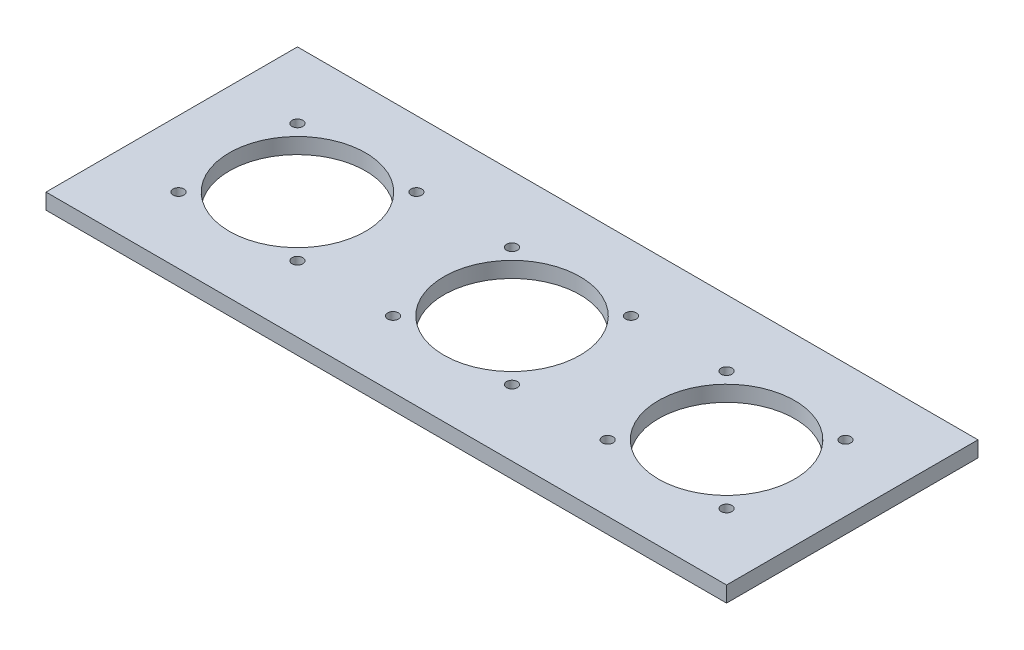
SolidWorks part; units mm, degrees
ref_plane "Front Plane" through (0, 0, 0) normal (0, 0, 1) x (1, 0, 0)
ref_plane "Top Plane" through (0, 0, 0) normal (0, 1, 0) x (1, 0, 0)
ref_plane "Right Plane" through (0, 0, 0) normal (1, 0, 0) x (0, 0, -1)
sketch "Sketch1" plane through (0, 0, 0) normal (0, 1, 0) x (1, 0, 0)
  line L1 (-206.248, -76.2) -> (206.248, -76.2)
  line L2 (-206.248, -76.2) -> (-206.248, 76.2)
  line L3 (-206.248, 76.2) -> (206.248, 76.2)
  line L4 (206.248, -76.2) -> (206.248, 76.2)
  line L5 (-206.248, -76.2) -> (206.248, 76.2) construction
  line L6 (-206.248, 76.2) -> (206.248, -76.2) construction
  point P0 (0, 0)
  dimension "D1" = 206.248
  dimension "D2" = 76.2
extrude "Boss-Extrude1" add sketch "Sketch1" along normal mid plane 9.525
sketch "Sketch2" plane through (0, 0, 0) normal (0, 1, 0) x (1, 0, 0)
  circle A0 centre (-130.048, 0) radius 41.275
  circle A1 centre (0, 0) radius 41.275
  circle A2 centre (130.048, 0) radius 41.275
  point P6 (0, 0)
  dimension "D1" = 82.55
  dimension "D2" = 82.55
  dimension "D3" = 82.55
  dimension "D4" = 130.048
  dimension "D5" = 260.096
extrude "Cut-Extrude2" cut sketch "Sketch2" against normal through all from offset 4.7625
hole_wizard "5/16-18 Tapped Hole1" positions "Sketch4" profile "Sketch3" tap size "5/16-18" standard "ANSI Inch"
sketch "Sketch4" plane through (0, 4.7625, 0) normal (0, 1, 0) x (1, 0, 0)
  line L0 (-166.0906, -36.0426) -> (-94.0054, -36.0426) construction
  line L1 (-94.0054, -36.0426) -> (-94.0054, 36.0426) construction
  line L2 (-94.0054, 36.0426) -> (-166.0906, 36.0426) construction
  line L3 (-166.0906, 36.0426) -> (-166.0906, -36.0426) construction
  line L4 (0, 0) -> (-94.0054, -36.0426) construction
  line L5 (206.248, -76.2) -> (206.248, 76.2) construction
  point P0 (-166.0906, -36.0426)
  point P1 (-94.0054, -36.0426)
  point P3 (-166.0906, 36.0426)
  point P5 (-94.0054, 36.0426)
  dimension "D1" = 300.2534
  dimension "D2" = 372.3386
  dimension "D3" = 40.1574
  dimension "D4" = 112.2426
sketch "Sketch3" plane through (-166.0906, 4.7625, 36.0426) normal (1, 0, 0) x (0, 0, 1)
  line L0 (0, 0) -> (0, 11.4861)
  line L1 (0, 11.4861) -> (3.2639, 9.525)
  line L2 (3.2639, 9.525) -> (3.2639, 0)
  line L5 (3.2639, 0) -> (0, 0)
  line L10 (0, 11.4861) -> (-3.2639, 9.525) construction
  line L11 (0, -6.35) -> (0, 107.95) construction
  dimension "Tap Drill Dia." = 6.5278
  dimension "Tap Drill Depth" = 9.525
  dimension "Drill Angle" = 118
cosmetic thread "Hole Thread1" parameters "D1"=15.875, "D2"=7.9375
cosmetic thread "Hole Thread2" parameters "D1"=15.875, "D2"=7.9375
cosmetic thread "Hole Thread3" parameters "D1"=15.875, "D2"=7.9375
cosmetic thread "Hole Thread4" parameters "D1"=15.875, "D2"=7.9375
hole_wizard "5/16-18 Tapped Hole2" positions "Sketch6" profile "Sketch5" tap size "5/16-18" standard "ANSI Inch"
sketch "Sketch6" plane through (0, 4.7625, 0) normal (0, 1, 0) x (1, 0, 0)
  line L0 (-36.0426, -36.0426) -> (36.0426, -36.0426) construction
  line L1 (36.0426, -36.0426) -> (36.0426, 36.0426) construction
  line L2 (36.0426, 36.0426) -> (-36.0426, 36.0426) construction
  line L3 (-36.0426, 36.0426) -> (-36.0426, -36.0426) construction
  line L4 (0, 0) -> (36.0426, -36.0426) construction
  circle A0 centre (-130.048, 0) radius 41.275 construction
  point P0 (-36.0426, -36.0426)
  point P1 (36.0426, -36.0426)
  point P3 (-36.0426, 36.0426)
  point P5 (36.0426, 36.0426)
  dimension "D1" = 94.0054
  dimension "D2" = 166.0906
  dimension "D3" = 36.0426
sketch "Sketch5" plane through (-36.0426, 4.7625, 36.0426) normal (1, 0, 0) x (0, 0, 1)
  line L0 (0, 0) -> (0, 11.4861)
  line L1 (0, 11.4861) -> (3.2639, 9.525)
  line L2 (3.2639, 9.525) -> (3.2639, 0)
  line L5 (3.2639, 0) -> (0, 0)
  line L10 (0, 11.4861) -> (-3.2639, 9.525) construction
  line L11 (0, -6.35) -> (0, 107.95) construction
  dimension "Tap Drill Dia." = 6.5278
  dimension "Tap Drill Depth" = 9.525
  dimension "Drill Angle" = 118
cosmetic thread "Hole Thread5" parameters "D1"=15.875, "D2"=7.9375
cosmetic thread "Hole Thread6" parameters "D1"=15.875, "D2"=7.9375
cosmetic thread "Hole Thread7" parameters "D1"=15.875, "D2"=7.9375
cosmetic thread "Hole Thread8" parameters "D1"=15.875, "D2"=7.9375
hole_wizard "5/16-18 Tapped Hole3" positions "Sketch8" profile "Sketch7" tap size "5/16-18" standard "ANSI Inch"
sketch "Sketch8" plane through (0, 4.7625, 0) normal (0, 1, 0) x (1, 0, 0)
  line L0 (94.0054, -36.0426) -> (166.0906, -36.0426) construction
  line L1 (166.0906, -36.0426) -> (166.0906, 36.0426) construction
  line L2 (166.0906, 36.0426) -> (94.0054, 36.0426) construction
  line L3 (94.0054, 36.0426) -> (94.0054, -36.0426) construction
  line L4 (0, 0) -> (166.0906, -36.0426) construction
  circle A0 centre (-166.0906, -36.0426) radius 3.2639 construction
  point P0 (94.0054, -36.0426)
  point P1 (166.0906, -36.0426)
  point P3 (94.0054, 36.0426)
  point P5 (166.0906, 36.0426)
  dimension "D1" = 260.096
  dimension "D2" = 332.1812
  dimension "D3" = 72.0852
  dimension "D4" = 94.0054
  dimension "D5" = 36.0426
sketch "Sketch7" plane through (94.0054, 4.7625, 36.0426) normal (1, 0, 0) x (0, 0, 1)
  line L0 (0, 0) -> (0, 11.4861)
  line L1 (0, 11.4861) -> (3.2639, 9.525)
  line L2 (3.2639, 9.525) -> (3.2639, 0)
  line L5 (3.2639, 0) -> (0, 0)
  line L10 (0, 11.4861) -> (-3.2639, 9.525) construction
  line L11 (0, -6.35) -> (0, 107.95) construction
  dimension "Tap Drill Dia." = 6.5278
  dimension "Tap Drill Depth" = 9.525
  dimension "Drill Angle" = 118
cosmetic thread "Hole Thread9" parameters "D1"=15.875, "D2"=7.9375
cosmetic thread "Hole Thread10" parameters "D1"=15.875, "D2"=7.9375
cosmetic thread "Hole Thread11" parameters "D1"=15.875, "D2"=7.9375
cosmetic thread "Hole Thread12" parameters "D1"=15.875, "D2"=7.9375
